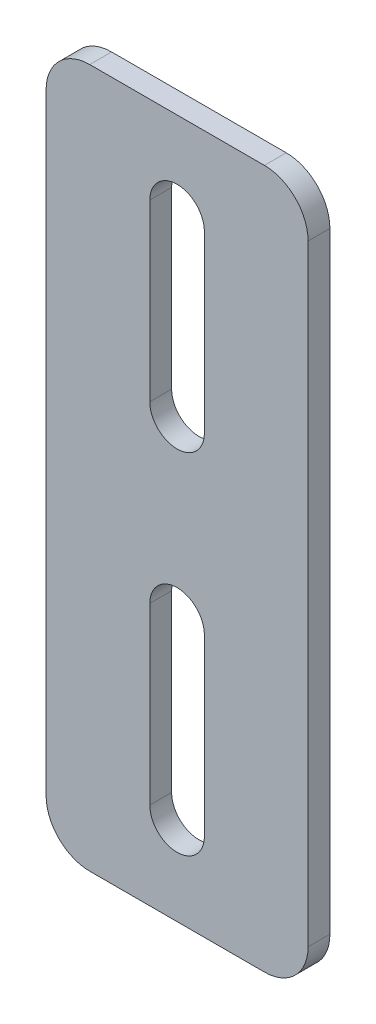
SolidWorks part; units mm, degrees
ref_plane "Front Plane" through (0, 0, 0) normal (0, 0, 1) x (1, 0, 0)
ref_plane "Top Plane" through (0, 0, 0) normal (0, 1, 0) x (1, 0, 0)
ref_plane "Right Plane" through (0, 0, 0) normal (1, 0, 0) x (0, 0, -1)
sketch "Sketch1" plane through (0, 0, 0) normal (0, 0, 1) x (1, 0, 0)
  line L1 (-19.05, -50.8) -> (19.05, -50.8)
  line L2 (-19.05, -50.8) -> (-19.05, 50.8)
  line L3 (-19.05, 50.8) -> (19.05, 50.8)
  line L4 (19.05, -50.8) -> (19.05, 50.8)
  line L5 (-19.05, -50.8) -> (19.05, 50.8) construction
  line L6 (-19.05, 50.8) -> (19.05, -50.8) construction
  point P0 (0, 0)
  dimension "D1" = 101.6
  dimension "D2" = 38.1
extrude "Boss-Extrude1" add sketch "Sketch1" along normal blind 3.175
fillet "Fillet1" radius 6.35 4 edges at (-19.05, -50.8, 1.5875) (19.05, -50.8, 1.5875) (-19.05, 50.8, 1.5875) (19.05, 50.8, 1.5875)
sketch "Sketch2" plane through (0, 0, 3.175) normal (0, 0, 1) x (1, 0, 0)
  line L0 (0, 38.1) -> (0, 12.7) construction
  line L1 (3.9688, 38.1) -> (3.9688, 12.7)
  line L2 (-3.9688, 38.1) -> (-3.9688, 12.7)
  line L3 (0, -12.7) -> (0, -38.1) construction
  line L4 (3.9688, -12.7) -> (3.9688, -38.1)
  line L5 (-3.9688, -12.7) -> (-3.9688, -38.1)
  line L6 (19.05, -44.45) -> (19.05, 44.45) construction
  line L7 (-19.05, 44.45) -> (-19.05, -44.45) construction
  line L8 (0, 12.7) -> (0, -12.7) construction
  arc A0 (3.9688, 38.1) -> (-3.9688, 38.1) centre (0, 38.1) ccw
  arc A1 (-3.9688, 12.7) -> (3.9688, 12.7) centre (0, 12.7) ccw
  arc A2 (3.9688, -12.7) -> (-3.9688, -12.7) centre (0, -12.7) ccw
  arc A3 (-3.9688, -38.1) -> (3.9688, -38.1) centre (0, -38.1) ccw
  point P2 (0, 25.4)
  point P7 (0, -25.4)
  dimension "D2" = 25.4
  dimension "D3" = 25.4
  dimension "D1" = 7.9375
extrude "Cut-Extrude1" cut sketch "Sketch2" against normal through all
